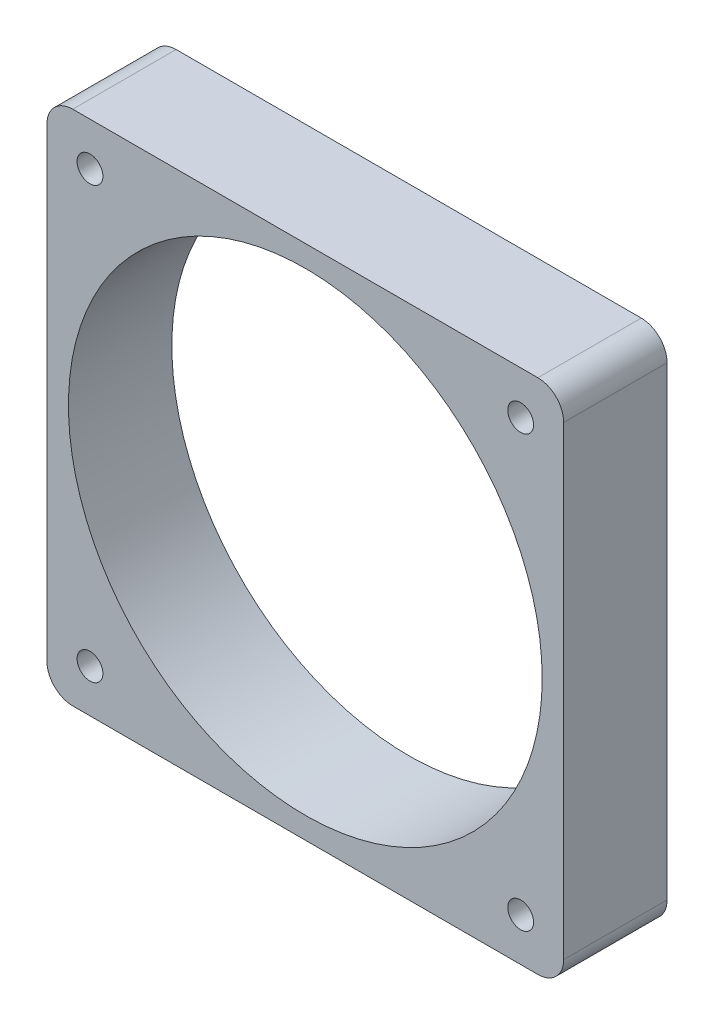
SolidWorks part; units mm, degrees
ref_plane "Front Plane" through (0, 0, 0) normal (0, 0, 1) x (1, 0, 0)
ref_plane "Top Plane" through (0, 0, 0) normal (0, 1, 0) x (1, 0, 0)
ref_plane "Right Plane" through (0, 0, 0) normal (1, 0, 0) x (0, 0, -1)
sketch "Sketch1" plane through (0, 0, 0) normal (0, 0, 1) x (1, 0, 0)
  line L0 (5.3333, 22) -> (5.3333, -38) construction
  line L1 (-24.6667, 22) -> (35.3333, 22)
  line L2 (-24.6667, 22) -> (-24.6667, -38)
  line L3 (-24.6667, -38) -> (35.3333, -38)
  line L4 (35.3333, 22) -> (35.3333, -38)
  line L5 (-24.6667, -8) -> (35.3333, -8) construction
  circle A0 centre (5.3333, -8) radius 27.5
  circle A1 centre (-19.6667, 17) radius 1.5
  circle A2 centre (30.3333, 17) radius 1.5
  circle A3 centre (-19.6667, -33) radius 1.5
  circle A4 centre (30.3333, -33) radius 1.5
  dimension "D2" = 55
  dimension "D3" = 3
  dimension "D1" = 60
  dimension "D4" = 5
  dimension "D5" = 5
  dimension "D6" = 5
  dimension "D7" = 5
extrude "Boss-Extrude1" add sketch "Sketch1" along normal blind 12
fillet "Fillet1" radius 3 4 edges at (-24.6667, -38, 6) (35.3333, -38, 6) (35.3333, 22, 6) (-24.6667, 22, 6)
